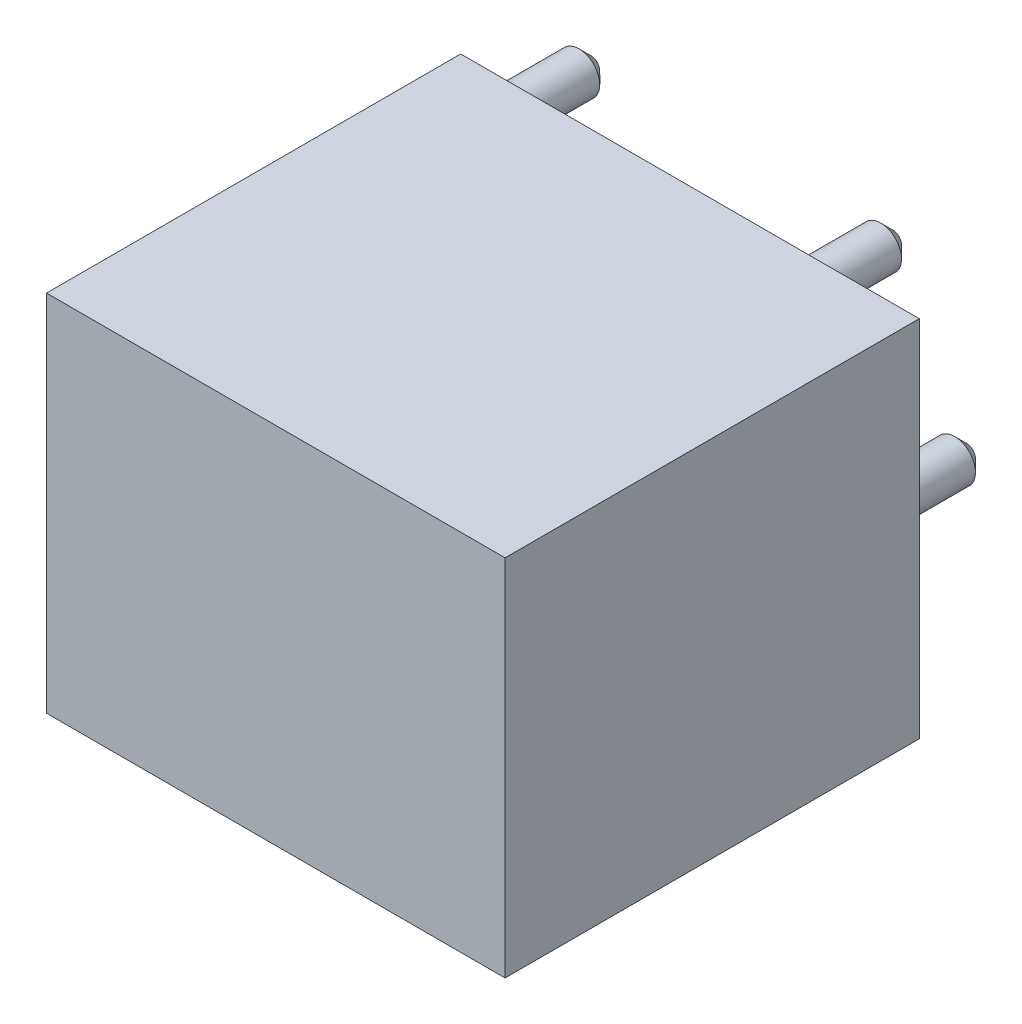
SolidWorks part; units mm, degrees
ref_plane "Top Plane" through (0, 0, 0) normal (0, 0, 1) x (1, 0, 0)
ref_plane "Right Plane" through (0, 0, 0) normal (0, 1, 0) x (1, 0, 0)
ref_plane "Front Plane" through (0, 0, 0) normal (1, 0, 0) x (0, 0, -1)
sketch "Sketch1" plane through (0, 0, 0) normal (0, 0, 1) x (1, 0, 0)
  line L0 (-7.75, 6.15) -> (7.75, -6.15) construction
  line L1 (-7.75, 6.15) -> (7.75, 6.15)
  line L2 (-7.75, 6.15) -> (-7.75, -6.15)
  line L3 (-7.75, -6.15) -> (7.75, -6.15)
  line L4 (7.75, 6.15) -> (7.75, -6.15)
  dimension "D1" = 15.5
  dimension "D2" = 12.3
extrude "Boss-Extrude1" add sketch "Sketch1" along normal mid plane 14
sketch "Sketch2" plane through (0, 0, -7) normal (0, 0, -1) x (-1, 0, 0)
  line L0 (-6.35, 0) -> (6.35, 0) construction
  line L1 (-3.85, 5) -> (6.35, 5) construction
  line L2 (-3.85, 5) -> (-3.85, -5) construction
  line L3 (-3.85, -5) -> (6.35, -5) construction
  line L4 (6.35, 5) -> (6.35, -5) construction
  circle A0 centre (-3.85, 5) radius 0.7
  circle A1 centre (6.35, 5) radius 0.7
  circle A2 centre (6.35, -5) radius 0.7
  circle A3 centre (-3.85, -5) radius 0.7
  circle A4 centre (-6.35, 0) radius 0.7
  dimension "D4" = 1.4
  dimension "D1" = 10
  dimension "D2" = 10.2
  dimension "D3" = 12.7
extrude "Boss-Extrude2" add sketch "Sketch2" along normal blind 3
chamfer "Chamfer1" distance 0.4 angle 45 5 edges at (-7.05, 5, -10) (-7.05, -5, -10) (3.15, 5, -10) (5.65, 0, -10) (3.15, -5, -10)
